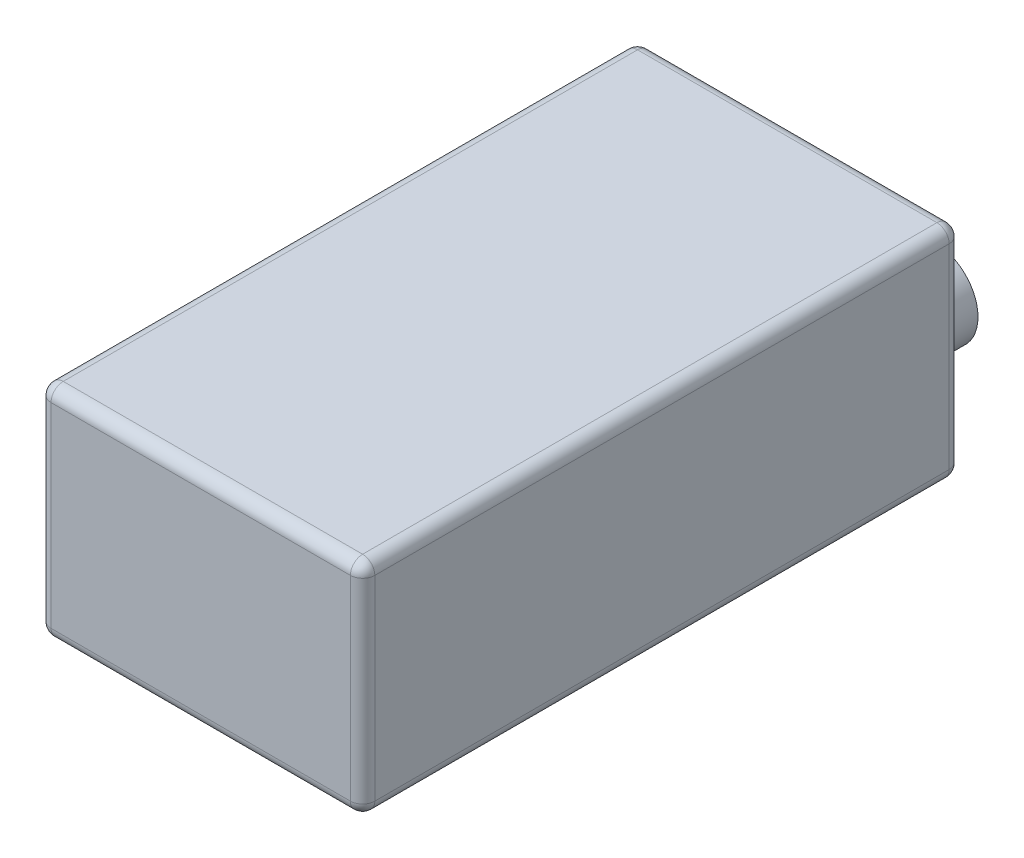
SolidWorks part; units mm, degrees
ref_plane "Plan de face" through (0, 0, 0) normal (0, 0, 1) x (1, 0, 0)
ref_plane "Plan de dessus" through (0, 0, 0) normal (0, 1, 0) x (1, 0, 0)
ref_plane "Plan de droite" through (0, 0, 0) normal (1, 0, 0) x (0, 0, -1)
sketch "Esquisse1" plane through (0, 0, 0) normal (0, 1, 0) x (1, 0, 0)
  line L1 (-13.25, 24.5) -> (13.25, 24.5)
  line L2 (-13.25, 24.5) -> (-13.25, -24.5)
  line L3 (-13.25, -24.5) -> (13.25, -24.5)
  line L4 (13.25, 24.5) -> (13.25, -24.5)
  line L5 (-13.25, 24.5) -> (13.25, -24.5) construction
  line L6 (-13.25, -24.5) -> (13.25, 24.5) construction
  point P0 (0, 0)
  dimension "D1" = 26.5
  dimension "D2" = 49
extrude "Boss.-Extru.1" add sketch "Esquisse1" along normal blind 18
fillet "Congé1" radius 1 12 edges at (0, 0, -24.5) (-13.25, 0, 0) (-13.25, 9, -24.5) (13.25, 0, 0) (0, 0, 24.5) (13.25, 18, 0) (0, 18, -24.5) (-13.25, 18, 0) (0, 18, 24.5) (13.25, 9, 24.5) (-13.25, 9, 24.5) (13.25, 9, -24.5)
sketch "Esquisse2" plane through (0, 0, -24.5) normal (0, 0, -1) x (-1, 0, 0)
  line L0 (0, 0) -> (0, 18) construction
  line L1 (-12.25, 18) -> (12.25, 18) construction
  line L2 (0, 18) -> (0, 9) construction
  line L3 (0, 9) -> (13.25, 9) construction
  line L4 (13.25, 17) -> (13.25, 1) construction
  line L5 (13.25, 9) -> (-13.25, 9) construction
  line L6 (-13.25, 1) -> (-13.25, 17) construction
  circle A0 centre (-8.1133, 9) radius 3.5
  dimension "D1" = 7
extrude "Boss.-Extru.2" add sketch "Esquisse2" along normal blind 3
mirror "Symétrie1" about plane through (0, 0, 0) normal (1, 0, 0) of "Boss.-Extru.2"
